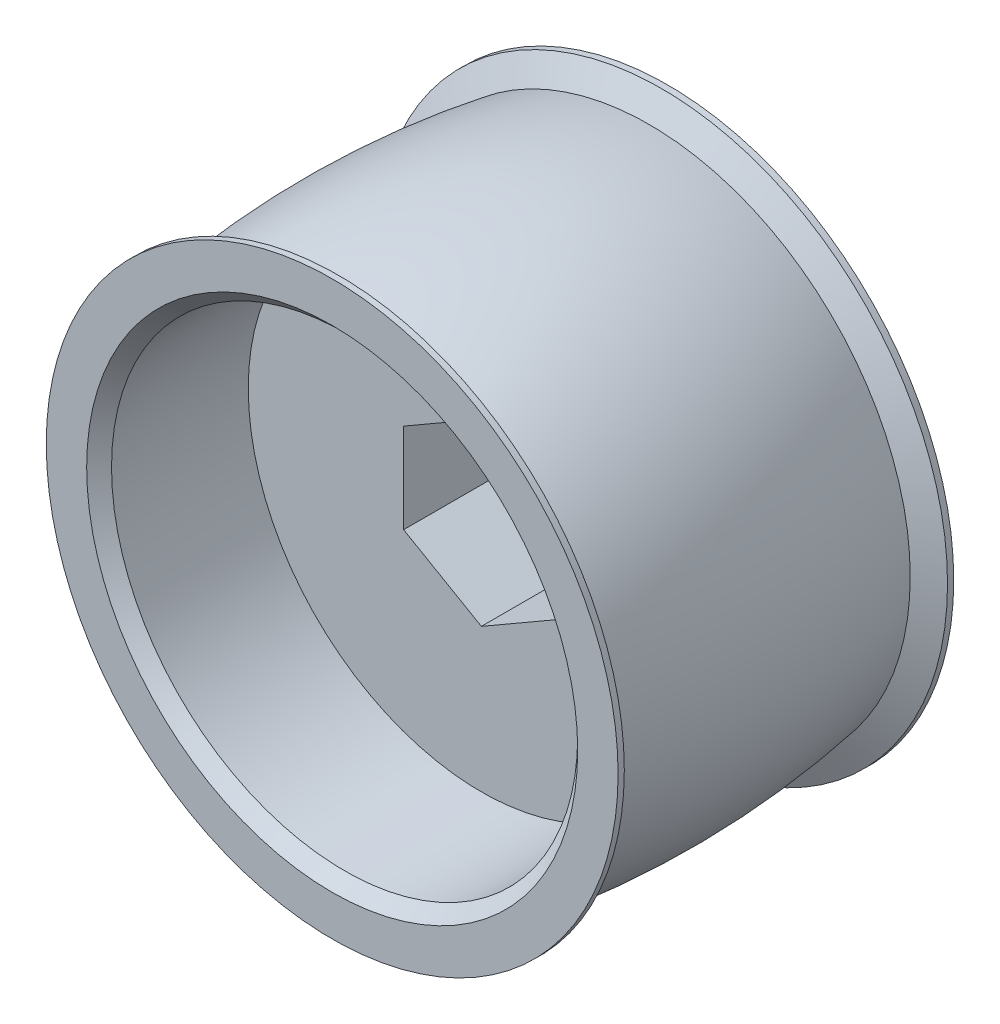
SolidWorks part; units mm, degrees
ref_plane "Plan de face" through (0, 0, 0) normal (0, 0, 1) x (1, 0, 0)
ref_plane "Plan de dessus" through (0, 0, 0) normal (0, 1, 0) x (1, 0, 0)
ref_plane "Plan de droite" through (0, 0, 0) normal (1, 0, 0) x (0, 0, -1)
sketch "Esquisse1" plane through (0, 0, 0) normal (0, 0, 1) x (1, 0, 0)
  circle A0 centre (0, 0) radius 2.15
  circle A1 centre (0, 0) radius 23
  dimension "D1" = 46
  dimension "D2" = 4.3
extrude "Boss.-Extru.1" add sketch "Esquisse1" along normal blind 15
sketch "Esquisse2" plane through (0, 0, 15) normal (0, 0, 1) x (1, 0, 0)
  circle A0 centre (0, 0) radius 23
  circle A1 centre (0, 0) radius 18.75
  circle A2 centre (0, 0) radius 23 construction
  dimension "D1" = 37.5
extrude "Boss.-Extru.2" add sketch "Esquisse2" along normal blind 12
sketch "Esquisse9" plane through (0, 0, 15) normal (0, 0, 1) x (1, 0, 0)
  line L0 (0, 0) -> (0, 14.4338) construction
  line L1 (6.25, -3.6084) -> (6.25, 3.6084)
  line L2 (6.25, 3.6084) -> (0, 7.2169)
  line L3 (0, 7.2169) -> (-6.25, 3.6084)
  line L4 (-6.25, 3.6084) -> (-6.25, -3.6084)
  line L5 (-6.25, -3.6084) -> (0, -7.2169)
  line L6 (0, -7.2169) -> (6.25, -3.6084)
  circle A0 centre (0, 0) radius 6.25 construction
  dimension "D1" = 12.5
extrude "Enlèv. mat.-Extru.9" cut sketch "Esquisse9" against normal offset from surface (13 mm away) 2 up to face at (23, 0, 0)
chamfer "Chanfrein1" distance 1 angle 45 1 edges at (18.75, 0, 27)
sketch "Esquisse10" plane through (0, 0, 0) normal (1, 0, 0) x (0, 0, -1)
  line L0 (-26.5, 23) -> (-0.5, 23)
  line L1 (0, 23) -> (-27, 23) construction
  line L2 (-0.5, 23) -> (-1.5, 21)
  line L3 (-1.5, 21) -> (-25.5, 21) construction
  line L4 (-25.5, 21) -> (-26.5, 23)
  line L5 (-19.6787, 22) -> (-7.7815, 22) construction
  line L6 (0, 0) -> (-50.6564, 0) construction
  arc A0 (-25.5, 21) -> (-1.5, 21) centre (-13.5, -50.5) cw
  dimension "D6" = 1
  dimension "D1" = 2
  dimension "D2" = 0.5
  dimension "D3" = 0.5
  dimension "D4" = 1
  dimension "D5" = 1
revolve "Enlèvement de matière-Révolution1" cut sketch "Esquisse10" angle 360 about L6
